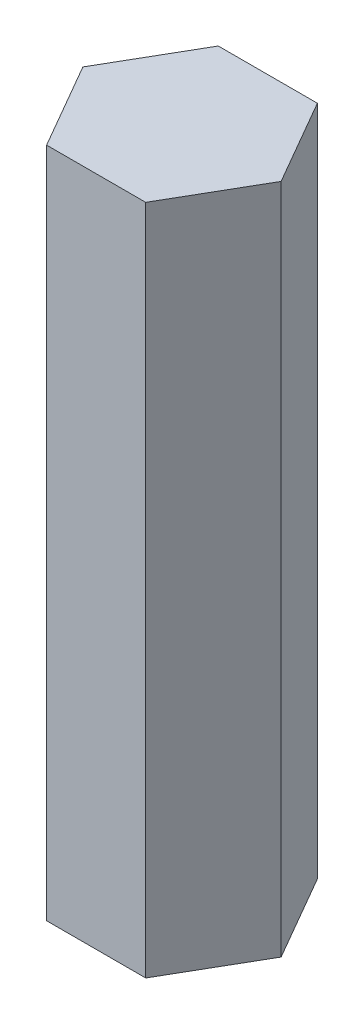
SolidWorks part; units mm, degrees
ref_plane "Front Plane" through (0, 0, 0) normal (0, 0, 1) x (1, 0, 0)
ref_plane "Top Plane" through (0, 0, 0) normal (0, 1, 0) x (1, 0, 0)
ref_plane "Right Plane" through (0, 0, 0) normal (1, 0, 0) x (0, 0, -1)
sketch "Sketch1" plane through (0, 0, 0) normal (0, 1, 0) x (1, 0, 0)
  line L1 (2.6558, 0) -> (1.3279, 2.3)
  line L2 (1.3279, 2.3) -> (-1.3279, 2.3)
  line L3 (-1.3279, 2.3) -> (-2.6558, 0)
  line L4 (-2.6558, 0) -> (-1.3279, -2.3)
  line L5 (-1.3279, -2.3) -> (1.3279, -2.3)
  line L6 (1.3279, -2.3) -> (2.6558, 0)
  circle A0 centre (0, 0) radius 2.3 construction
extrude "Boss-Extrude1" add sketch "Sketch1" along normal blind 18
